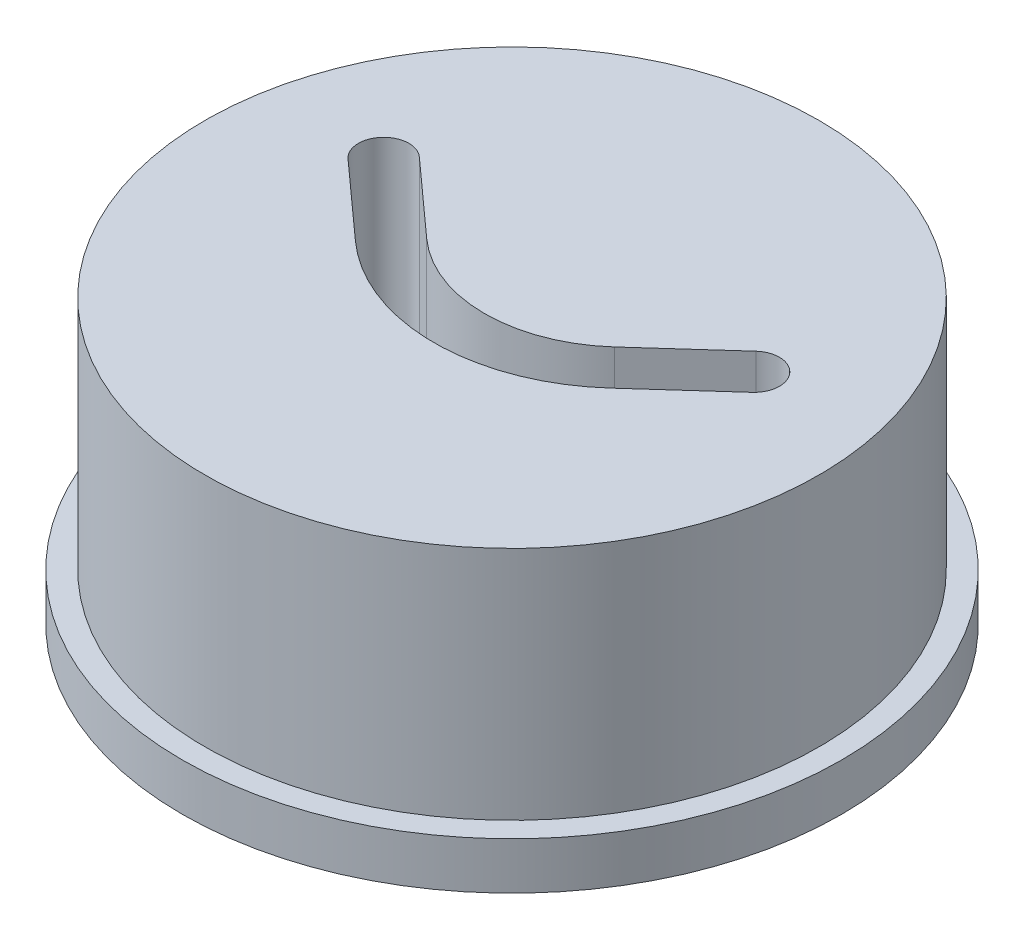
SolidWorks part; units mm, degrees
ref_plane "Front Plane" through (0, 0, 0) normal (0, 0, 1) x (1, 0, 0)
ref_plane "Top Plane" through (0, 0, 0) normal (0, 1, 0) x (1, 0, 0)
ref_plane "Right Plane" through (0, 0, 0) normal (1, 0, 0) x (0, 0, -1)
sketch "Sketch2" plane through (0, 0, 0) normal (0, 1, 0) x (1, 0, 0)
  line L0 (-6.985, 0) -> (6.985, 0) construction
  line L10 (0, 6.985) -> (0, -6.985) construction
  line L13 (0, -6.985) -> (0, 0) construction
  line L14 (-13.081, 3.175) -> (13.081, 3.175) construction
  line L15 (0, -4.445) -> (0, 3.175) construction
  line L16 (-13.081, 3.175) -> (-8.0591, -1.3498)
  line L17 (13.081, 3.175) -> (8.0591, -1.3498)
  line L18 (-11.8908, 4.4959) -> (-6.8689, -0.0289)
  line L19 (11.8908, 4.4959) -> (6.8689, -0.0289)
  line L21 (-12.4859, 3.8355) -> (12.4859, 3.8355) construction
  circle A0 centre (0, 0) radius 20.701
  arc A9 (-8.0591, -1.3498) -> (8.0591, -1.3498) centre (0, 7.5946) ccw
  arc A10 (-13.081, 3.175) -> (-11.8908, 4.4959) centre (-12.4859, 3.8355) cw
  arc A11 (-6.8689, -0.0289) -> (6.8689, -0.0289) centre (0, 7.5946) ccw
  arc A12 (11.8908, 4.4959) -> (13.081, 3.175) centre (12.4859, 3.8355) cw
  point P13 (14.506, 14.7685)
  point P36 (0, 3.175)
  point P37 (-33.8663, 15.7634)
  point P42 (0, -4.445)
  point P47 (0, 3.175)
  dimension "D1" = 41.402
  dimension "D4" = 24.9718
  dimension "D9" = 12.0396
  dimension "D11" = 0.889
  dimension "D12" = 10.2616
  dimension "D3" = 3.175
  dimension "D10" = 6.7597
extrude "Boss-Extrude1" add sketch "Sketch2" along normal blind 19.05
sketch "Sketch14" plane through (0, 19.05, 0) normal (0, 1, 0) x (1, 0, 0)
  line L37 (8.6032, -1.9537) -> (13.6251, 2.5712)
  line L38 (11.3468, 5.0997) -> (6.3249, 0.5749)
  line L39 (-6.3249, 0.5749) -> (-11.3468, 5.0997)
  line L40 (-13.6251, 2.5712) -> (-8.6032, -1.9537)
  line L41 (8.6032, -1.9537) -> (13.6251, 2.5712)
  line L42 (11.3468, 5.0997) -> (6.3249, 0.5749)
  line L43 (-6.3249, 0.5749) -> (-11.3468, 5.0997)
  line L44 (-13.6251, 2.5712) -> (-8.6032, -1.9537)
  arc A43 (13.6251, 2.5712) -> (11.3468, 5.0997) centre (12.4859, 3.8355) ccw
  arc A44 (-6.3249, 0.5749) -> (6.3249, 0.5749) centre (0, 7.5946) ccw
  arc A45 (-11.3468, 5.0997) -> (-13.6251, 2.5712) centre (-12.4859, 3.8355) ccw
  arc A46 (-8.6032, -1.9537) -> (8.6032, -1.9537) centre (0, 7.5946) ccw
  arc A47 (13.6251, 2.5712) -> (11.3468, 5.0997) centre (12.4859, 3.8355) ccw
  arc A48 (-6.3249, 0.5749) -> (6.3249, 0.5749) centre (0, 7.5946) ccw
  arc A49 (-11.3468, 5.0997) -> (-13.6251, 2.5712) centre (-12.4859, 3.8355) ccw
  arc A50 (-8.6032, -1.9537) -> (8.6032, -1.9537) centre (0, 7.5946) ccw
  dimension "D1" = 0.8128
extrude "Cut-Extrude2" cut sketch "Sketch14" against normal blind 12.7
sketch "Sketch15" plane through (0, 0, 0) normal (0, -1, 0) x (1, 0, 0)
  line L0 (-13.081, -3.175) -> (-8.0591, 1.3498) construction
  line L1 (-6.8689, 0.0289) -> (-11.8908, -4.4959) construction
  line L2 (11.8908, -4.4959) -> (6.8689, 0.0289) construction
  line L3 (8.0591, 1.3498) -> (13.081, -3.175) construction
  line L4 (-13.081, -3.175) -> (-8.0591, 1.3498)
  line L5 (-6.8689, 0.0289) -> (-11.8908, -4.4959)
  line L6 (11.8908, -4.4959) -> (6.8689, 0.0289)
  line L7 (8.0591, 1.3498) -> (13.081, -3.175)
  circle A0 centre (0, 0) radius 22.225
  arc A1 (8.0591, 1.3498) -> (-8.0591, 1.3498) centre (0, -7.5946) ccw construction
  arc A2 (-13.081, -3.175) -> (-11.8908, -4.4959) centre (-12.4859, -3.8355) ccw construction
  arc A3 (6.8689, 0.0289) -> (-6.8689, 0.0289) centre (0, -7.5946) ccw construction
  arc A4 (11.8908, -4.4959) -> (13.081, -3.175) centre (12.4859, -3.8355) ccw construction
  arc A5 (8.0591, 1.3498) -> (-8.0591, 1.3498) centre (0, -7.5946) ccw
  arc A6 (-13.081, -3.175) -> (-11.8908, -4.4959) centre (-12.4859, -3.8355) ccw
  arc A7 (6.8689, 0.0289) -> (-6.8689, 0.0289) centre (0, -7.5946) ccw
  arc A8 (11.8908, -4.4959) -> (13.081, -3.175) centre (12.4859, -3.8355) ccw
  dimension "D1" = 44.45
extrude "Boss-Extrude2" add sketch "Sketch15" against normal blind 3.175
